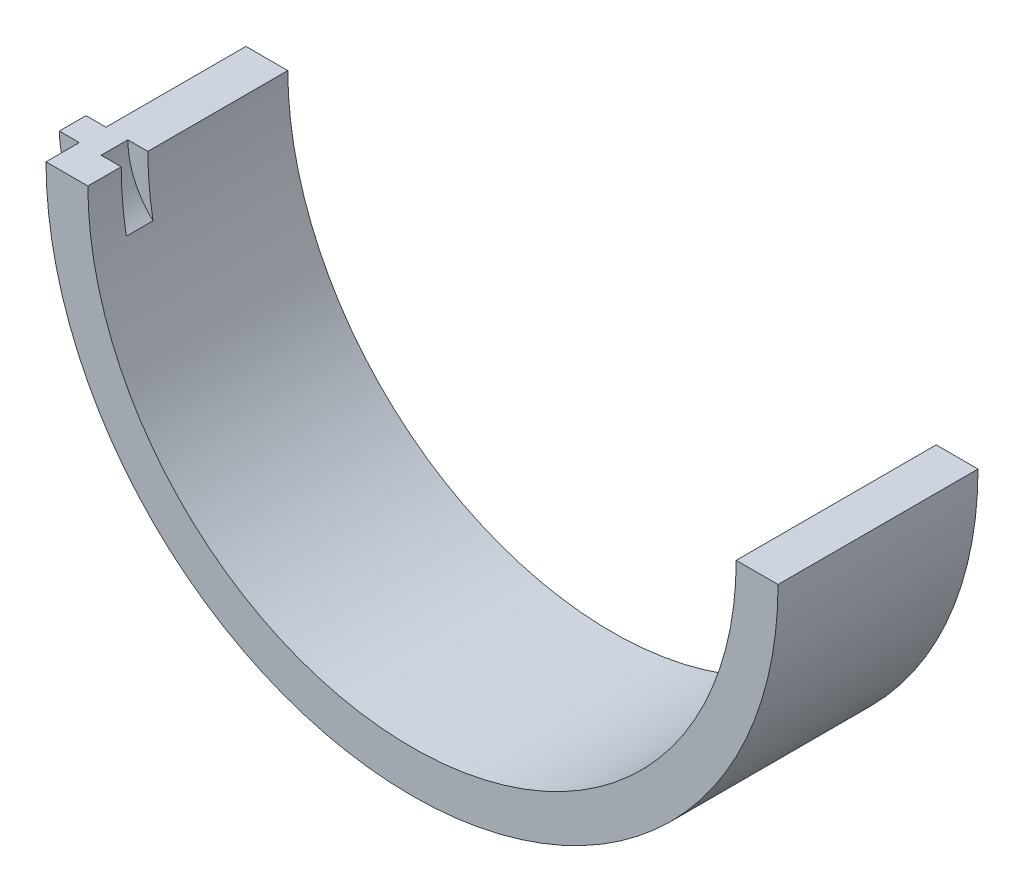
SolidWorks part; units mm, degrees
material "201 Annealed Stainless Steel (SS)"
ref_plane "Front Plane" through (0, 0, 0) normal (0, 0, 1) x (1, 0, 0)
ref_plane "Top Plane" through (0, 0, 0) normal (0, 1, 0) x (1, 0, 0)
ref_plane "Right Plane" through (0, 0, 0) normal (1, 0, 0) x (0, 0, -1)
sketch "Sketch1" plane through (0, 0, 0) normal (0, 0, 1) x (1, 0, 0)
  line L0 (34.8742, 34.8742) -> (-34.8742, 34.8742) construction
  line L1 (-30.8864, 34.8742) -> (-34.8742, 34.8742)
  line L2 (30.8864, 34.8742) -> (34.8742, 34.8742)
  line L3 (0, 0) -> (-12.7, 0) construction
  circle A0 centre (0, 34.8742) radius 34.8742 construction
  circle A1 centre (0, 34.8742) radius 30.8864 construction
  arc A2 (-34.8742, 34.8742) -> (34.8742, 34.8742) centre (0, 34.8742) ccw
  arc A3 (30.8864, 34.8742) -> (-30.8864, 34.8742) centre (0, 34.8742) cw
  dimension "D1" = 3.9878
  dimension "D2" = 61.7728
  dimension "D3" = 12.7
extrude "Boss-Extrude1" add sketch "Sketch1" against normal blind 19.05
sketch "Sketch2" plane through (0, 0, 0) normal (0, 1, 0) x (1, 0, 0)
  line L0 (34.8742, 0) -> (-34.8742, 19.05) construction
  circle A0 centre (0, 9.525) radius 1.4986
  dimension "D1" = 2.9972
extrude "Cut-Extrude1" [suppressed] cut sketch "Sketch2" along normal up to next
sketch "Sketch3" [suppressed] plane through (0, 34.8742, 0) normal (0, 1, 0) x (1, 0, 0)
  line L0 (30.8864, 19.05) -> (30.8864, 0) construction
  line L1 (30.8864, 9.525) -> (30.5054, 9.525) construction
  line L2 (30.8861, 10.9744) -> (30.8861, 8.0756)
  arc A0 (30.8861, 10.9744) -> (30.8861, 8.0756) centre (30.5054, 9.525) cw
  circle A1 centre (0, 9.525) radius 1.4986 construction
  dimension "D1" = 0.0003
  dimension "D2" = 0.381
ref_plane "Plane1" through (0, 0, -9.525) normal (0, 0, 1) x (1, 0, 0)
sketch "Sketch4" [suppressed] plane through (0, 0, -9.525) normal (0, 0, 1) x (1, 0, 0)
  line L0 (30.8864, 34.8742) -> (30.5054, 34.8742) construction
  arc A0 (-30.8864, 34.8742) -> (30.8864, 34.8742) centre (0, 34.8767) ccw
  dimension "D1" = 0.0025
sweep "Cut-Sweep1" [suppressed] cut profiles "Sketch3" path "Sketch4"
ref_plane "Plane2" through (0, 0, -3.175) normal (0, 0, 1) x (1, 0, 0)
sketch "Sketch5" plane through (0, 0, -3.175) normal (0, 0, 1) x (1, 0, 0)
  line L0 (34.8742, 34.8742) -> (-34.8742, 34.8742) construction
  line L1 (34.8742, 34.8742) -> (36.7792, 34.8742) construction
  line L2 (36.7792, 34.8742) -> (36.7792, 37.4052) construction
  line L3 (0, 34.8742) -> (0, 0) construction
  line L4 (-34.8742, 34.8742) -> (-36.7792, 34.8742)
  arc A0 (34.8742, 34.8742) -> (34.4398, 29.387) centre (0, 34.8742) cw construction
  arc A1 (36.7792, 34.8742) -> (34.4398, 29.387) centre (29.1742, 34.8742) cw construction
  arc A2 (-34.8742, 34.8742) -> (-34.4398, 29.387) centre (0, 34.8742) ccw
  arc A3 (-36.7792, 34.8742) -> (-34.4398, 29.387) centre (-29.1742, 34.8742) ccw
  dimension "D1" = 2.531
  dimension "D2" = 1.905
extrude "Boss-Extrude2" add sketch "Sketch5" against normal blind 2.54
sketch "Sketch6" plane through (0, 0, -3.175) normal (0, 0, 1) x (1, 0, 0)
  line L0 (34.8742, 34.8742) -> (-34.8742, 34.8742) construction
  line L1 (34.4398, 29.387) -> (30.3951, 29.387) construction
  line L2 (30.8864, 34.8742) -> (32.7914, 34.8742) construction
  line L4 (0, 34.8742) -> (0, 0) construction
  line L5 (-30.8864, 34.8742) -> (-32.7914, 34.8742)
  arc A0 (30.8864, 34.8742) -> (30.3951, 29.387) centre (0, 34.8742) cw construction
  arc A1 (32.7914, 34.8742) -> (30.3951, 29.387) centre (25.3108, 34.8742) cw construction
  arc A2 (-30.8864, 34.8742) -> (-30.3951, 29.387) centre (0, 34.8742) ccw
  arc A3 (-32.7914, 34.8742) -> (-30.3951, 29.387) centre (-25.3108, 34.8742) ccw
extrude "Cut-Extrude2" cut sketch "Sketch6" against normal blind 2.54 contours L2 A1 A0 | L5 A3 A2
ref_plane "Plane3" through (0, 0, -9.525) normal (0, 0, -1) x (-1, 0, 0)
